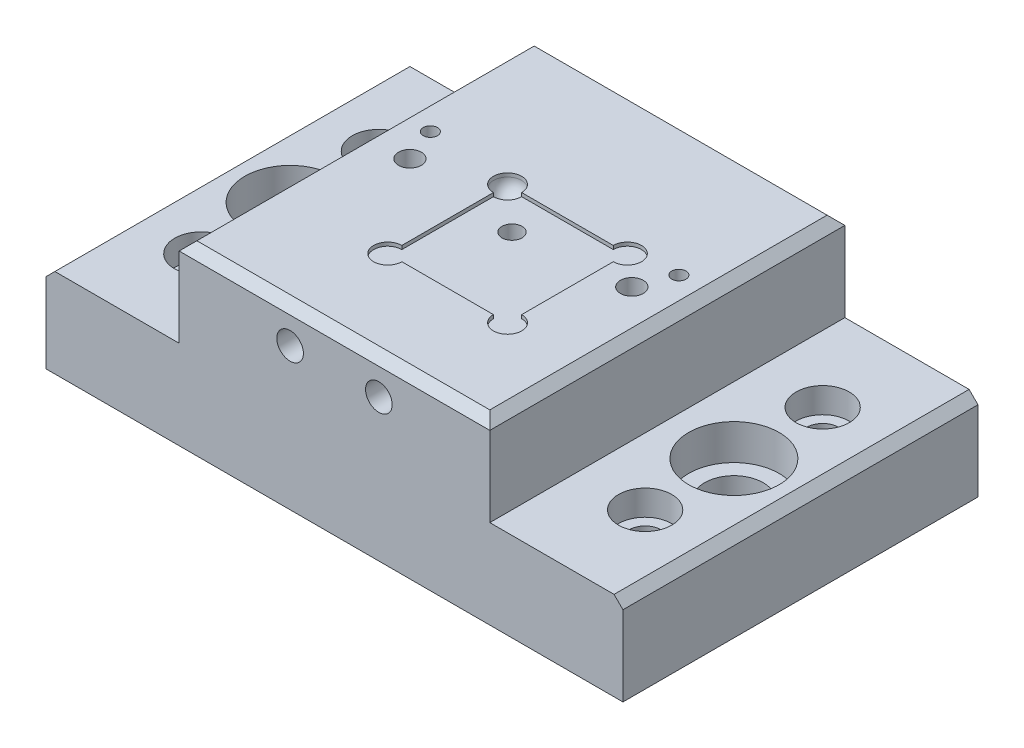
SolidWorks part; units mm, degrees
other "DetailItem1"
ref_plane "Front Plane" through (0, 0, 0) normal (0, 0, 1) x (1, 0, 0)
ref_plane "Top Plane" through (0, 0, 0) normal (0, 1, 0) x (1, 0, 0)
ref_plane "Right Plane" through (0, 0, 0) normal (1, 0, 0) x (0, 0, -1)
sketch "Sketch1" plane through (0, 0, 0) normal (0, 0, 1) x (1, 0, 0)
  line L1 (0, 0) -> (65, 0)
  line L2 (0, 0) -> (0, 10)
  line L3 (15, 20) -> (50, 20)
  line L4 (65, 0) -> (65, 10)
  line L7 (0, 10) -> (15, 10)
  line L8 (15, 20) -> (15, 10)
  line L11 (65, 10) -> (50, 10)
  line L12 (50, 20) -> (50, 10)
  dimension "D1" = 65
  dimension "D2" = 10
  dimension "D3" = 15
  dimension "D4" = 15
  dimension "D5" = 10
  dimension "D6" = 10
extrude "Boss-Extrude1" add sketch "Sketch1" along normal blind 40
sketch "Sketch2" plane through (0, 20, 0) normal (0, 1, 0) x (1, 0, 0)
  line L0 (29.5875, -16) -> (39.91, -16)
  line L1 (28, -27.91) -> (28, -17.5875)
  line L4 (50, 0) -> (15, 0) construction
  line L7 (0, -40) -> (0, 0) construction
  line L11 (29.59, -29.5) -> (39.91, -29.5)
  line L12 (41.5, -17.59) -> (41.5, -27.91)
  arc A0 (29.5875, -16) -> (28, -17.5875) centre (28, -16) ccw
  arc A1 (41.5, -17.59) -> (39.91, -16) centre (41.5, -16) ccw
  arc A2 (39.91, -29.5) -> (41.5, -27.91) centre (41.5, -29.5) ccw
  arc A3 (28, -27.91) -> (29.59, -29.5) centre (28, -29.5) ccw
  dimension "D7" = 3.175
  dimension "D10" = 16
  dimension "D2" = 13.5
  dimension "D3" = 3.18
  dimension "D4" = 13.5
  dimension "D5" = 3.18
  dimension "D6" = 3.18
  dimension "D17" = 28
extrude "Cut-Extrude1" cut sketch "Sketch2" against normal blind 0.4064
sketch "Sketch3" plane through (0, 10, 0) normal (0, 1, 0) x (1, 0, 0)
  line L0 (0, -40) -> (0, 0) construction
  line L2 (15, -40) -> (0, -40) construction
  circle A0 centre (7.5, -30) radius 1.8
  circle A1 centre (57.5, -30) radius 1.8
  circle A2 centre (7.5, -10) radius 1.8
  circle A3 centre (57.5, -10) radius 1.8
  dimension "D7" = 3.6
  dimension "D1" = 50
  dimension "D2" = 0
  dimension "D5" = 7.5
  dimension "D6" = 10
  dimension "D9" = 20
  dimension "D10" = 20
  dimension "D11" = 50
  dimension "D12" = 10
extrude "Cut-Extrude2" cut sketch "Sketch3" against normal through all
sketch "Sketch5" plane through (0, 19.5936, 0) normal (0, 1, 0) x (1, 0, 0)
  line L0 (65, -40) -> (65, 0) construction
  line L1 (50, -40) -> (15, -40) construction
  circle A0 centre (32.5, -20) radius 1.1303
  dimension "D1" = 2.2606
  dimension "D2" = 32.5
  dimension "D3" = 20
extrude "Cut-Extrude3" cut sketch "Sketch5" against normal blind 10
sketch "Sketch7" plane through (0, 0, 0) normal (0, 0, 1) x (1, 0, 0)
  line L0 (50, 20) -> (15, 20) construction
  line L1 (65, 0) -> (65, 10) construction
  circle A0 centre (32.5, 10) radius 1.1303
  dimension "D1" = 2.2606
  dimension "D2" = 10
  dimension "D3" = 32.5
extrude "Cut-Extrude4" cut sketch "Sketch7" along normal blind 22
chamfer "Chamfer1" distance 1 angle 45 6 edges at (15, 20, 20) (32.5, 20, 0) (50, 20, 20) (32.5, 20, 40) (0, 10, 20) (65, 10, 20)
sketch "Sketch8" plane through (0, 0, 0) normal (0, 0, -1) x (-1, 0, 0)
  line L0 (-50, 10) -> (-50, 19) construction
  line L1 (-49, 20) -> (-16, 20) construction
  circle A0 centre (-37.5, 16) radius 1.5
  circle A1 centre (-27.5, 16) radius 1.5
  dimension "D1" = 3
  dimension "D2" = 3
  dimension "D3" = 10
  dimension "D4" = 12.5
  dimension "D5" = 4
extrude "Cut-Extrude5" cut sketch "Sketch8" against normal through all
sketch "Sketch9" plane through (0, 0, 0) normal (0, -1, 0) x (1, 0, 0)
  line L0 (33.6303, 0) -> (31.3697, 0) construction
  line L1 (20.175, -4.5) -> (44.825, -4.5)
  line L2 (17, 35.5) -> (17, 6.0875)
  line L3 (18.5875, 4.5) -> (46.4125, 4.5)
  line L4 (48, 35.5) -> (48, 6.0875)
  line L5 (0, 40) -> (0, 0) construction
  line L6 (0, 40) -> (65, 40) construction
  line L7 (65, 40) -> (65, 0) construction
  line L8 (17, 35.5) -> (17, 40)
  line L9 (17, 40) -> (20.175, 40)
  line L10 (20.175, -4.5) -> (20.175, 40)
  line L11 (0, 0) -> (65, 0) construction
  line L13 (48, 35.5) -> (48, 40)
  line L14 (48, 40) -> (44.825, 40)
  line L15 (44.825, -4.5) -> (44.825, 40)
  arc A0 (17, 6.0875) -> (18.5875, 4.5) centre (17, 4.5) ccw
  arc A3 (46.4125, 4.5) -> (48, 6.0875) centre (48, 4.5) ccw
  dimension "D5" = 3.175
  dimension "D6" = 3.175
  dimension "D7" = 3.175
  dimension "D8" = 3.175
  dimension "D1" = 31
  dimension "D2" = 31
  dimension "D3" = 4.5
  dimension "D4" = 17
  dimension "D9" = 20.175
  dimension "D10" = 4.5
  dimension "D11" = 31
  dimension "D12" = 4.5
  dimension "D13" = 4.5
  dimension "D14" = 17
sketch "Sketch10" plane through (0, 20, 0) normal (0, 1, 0) x (1, 0, 0)
  line L0 (50, -40) -> (50, 0) construction
  line L2 (15, -40) -> (15, 0) construction
  line L7 (39.91, -16) -> (29.5875, -16) construction
  circle A1 centre (18.5, -15.2) radius 0.8
  circle A3 centre (46.5, -15.2) radius 0.8
  dimension "D2" = 1.6
  dimension "D4" = 3.5
  dimension "D7" = 3.5
extrude "Cut-Extrude7" cut sketch "Sketch10" against normal blind 8
sketch "Sketch12" plane through (0, 10, 0) normal (0, 1, 0) x (1, 0, 0)
  circle A0 centre (7.5, -30) radius 3
  circle A1 centre (57.5, -30) radius 3
  circle A2 centre (7.5, -10) radius 3
  circle A3 centre (57.5, -10) radius 3
  dimension "D3" = 6
extrude "Cut-Extrude9" cut sketch "Sketch12" against normal blind 2.8448
sketch "Sketch14" plane through (0, 10, 0) normal (0, 1, 0) x (1, 0, 0)
  line L0 (0, 0) -> (65, 0) construction
  line L1 (0, -40) -> (0, 0) construction
  circle A1 centre (7.5, -20) radius 3.3
  dimension "D3" = 6.6
  dimension "D1" = 20
  dimension "D2" = 7.5
extrude "Cut-Extrude11" cut sketch "Sketch14" against normal through all
sketch "Sketch15" plane through (0, 10, 0) normal (0, 1, 0) x (1, 0, 0)
  circle A0 centre (7.5, -20) radius 5.1
  dimension "D1" = 10.2
extrude "Cut-Extrude12" cut sketch "Sketch15" against normal blind 4
sketch "Sketch16" plane through (0, 10, 0) normal (0, 1, 0) x (1, 0, 0)
  line L0 (65, 0) -> (65, -40) construction
  line L1 (0, 0) -> (65, 0) construction
  circle A0 centre (57.5, -20) radius 3.3
  dimension "D3" = 6.6
  dimension "D1" = 7.5
  dimension "D2" = 20
extrude "Cut-Extrude13" cut sketch "Sketch16" against normal through all
sketch "Sketch17" plane through (0, 10, 0) normal (0, 1, 0) x (1, 0, 0)
  circle A0 centre (57.5, -20) radius 5.1
  dimension "D1" = 10.2
extrude "Cut-Extrude14" cut sketch "Sketch17" against normal blind 4
sketch "Sketch19" plane through (0, 19.5936, 0) normal (0, 1, 0) x (1, 0, 0)
  line L0 (29.5875, -16) -> (26.4125, -16)
  arc A0 (29.5875, -16) -> (26.4125, -16) centre (28, -16) cw
  arc A1 (29.5875, -16) -> (28, -17.5875) centre (28, -16) ccw construction
  arc A2 (29.5875, -16) -> (28, -17.5875) centre (28, -16) ccw construction
revolve "Cut-Revolve1" cut sketch "Sketch19" angle 360 about L0
hole_wizard "#5-40 Tapped Hole1" positions "Sketch21" profile "Sketch20" tap size "#5-40" standard "ANSI Inch"
sketch "Sketch21" plane through (0, 20, 0) normal (0, 1, 0) x (1, 0, 0)
  line L0 (50, -40) -> (50, 0) construction
  line L1 (15, -40) -> (15, 0) construction
  line L2 (15, 0) -> (50, 0) construction
  point P0 (20, -19)
  point P2 (45, -19)
  dimension "D1" = 5
  dimension "D2" = 5
  dimension "D3" = 19
sketch "Sketch20" plane through (20, 20, 19) normal (1, 0, 0) x (0, 0, 1)
  line L0 (0, 0) -> (0, 15.7745)
  line L1 (0, 15.7745) -> (1.289, 15)
  line L2 (1.289, 15) -> (1.289, 0)
  line L5 (1.289, 0) -> (0, 0)
  line L10 (0, 15.7745) -> (-1.2891, 15) construction
  line L11 (0, -6.35) -> (0, 107.95) construction
  dimension "Tap Drill Dia." = 2.5781
  dimension "Tap Drill Depth" = 15
  dimension "Drill Angle" = 118
cosmetic thread "Hole Thread1" parameters "D1"=12, "D2"=3.175
cosmetic thread "Hole Thread2" parameters "D1"=12, "D2"=3.175
sketch "Sketch28" plane through (0, 0, 0) normal (0, 0, -1) x (-1, 0, 0)
  circle A0 centre (-32.5, 10) radius 2.54
  dimension "D1" = 5.08
extrude "Cut-Extrude15" cut sketch "Sketch28" against normal blind 5
